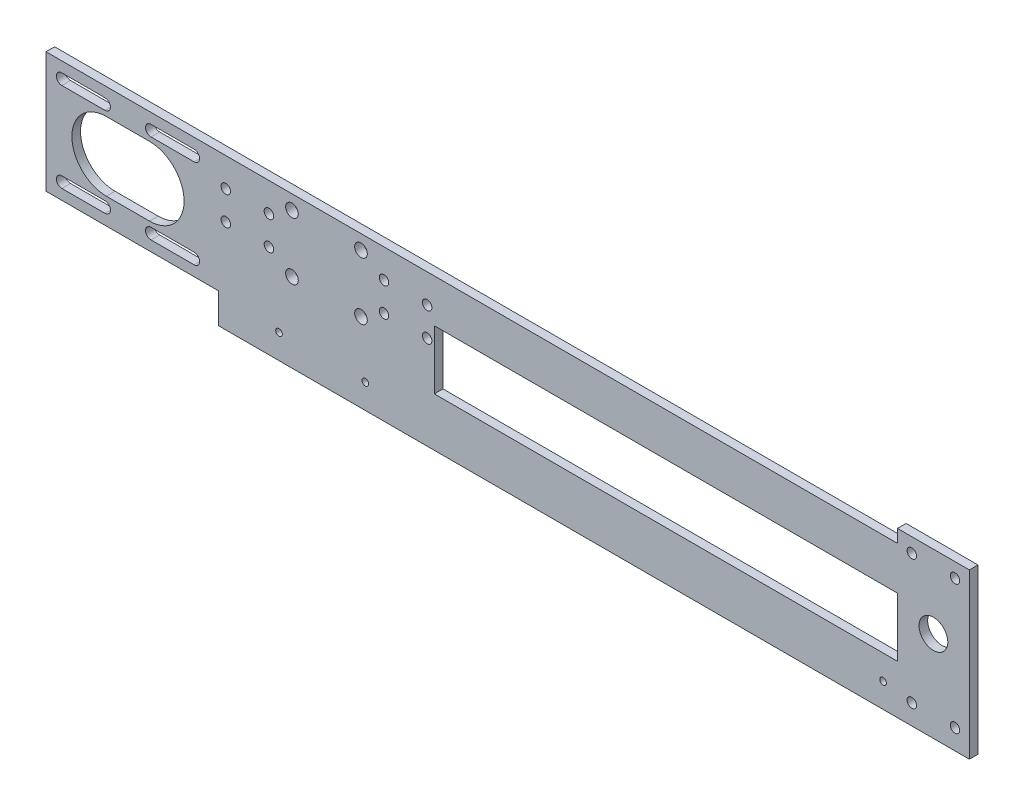
SolidWorks part; units mm, degrees
material "Thornel Mat VMA"
ref_plane "前视基准面" through (0, 0, 0) normal (0, 0, 1) x (1, 0, 0)
ref_plane "上视基准面" through (0, 0, 0) normal (0, 1, 0) x (1, 0, 0)
ref_plane "右视基准面" through (0, 0, 0) normal (1, 0, 0) x (0, 0, -1)
sketch "草图1" plane through (0, 0, 0) normal (0, 0, 1) x (1, 0, 0)
  line L1 (0, 0) -> (75, 0)
  line L2 (0, 0) -> (0, 30)
  line L3 (0, 30) -> (75, 30)
  line L4 (75, 0) -> (75, 30)
  dimension "D1" = 75
  dimension "D2" = 30
extrude "凸台-拉伸1" add sketch "草图1" along normal blind 3
sketch "草图2" plane through (0, 0, 3) normal (0, 0, 1) x (1, 0, 0)
  line L0 (0, 30) -> (75, 0)
  line L2 (25.5, 25) -> (49.5, 25)
  line L3 (25.5, 25) -> (25.5, 5)
  line L4 (25.5, 5) -> (49.5, 5)
  line L5 (49.5, 25) -> (49.5, 5)
  line L6 (25.5, 25) -> (49.5, 5) construction
  line L7 (25.5, 5) -> (49.5, 25) construction
  point P4 (37.5, 15)
  dimension "D1" = 24
  dimension "D2" = 20
sketch "草图3" plane through (0, 0, 3) normal (0, 0, 1) x (1, 0, 0)
  point P0 (25.5, 25)
  point P3 (49.5, 25)
  point P6 (49.5, 5)
  point P9 (25.5, 5)
hole_wizard "孔1" positions "草图3" profile "草图4" legacy end condition up to next
sketch "草图4" plane through (25.5, 25, 3) normal (1, 0, 0) x (0, -1, 0)
  line L0 (0, 0) -> (0, 3)
  line L1 (0, 3) -> (2.2, 3)
  line L2 (2.2, 3) -> (2.2, 0)
  line L3 (2.2, 0) -> (0, 0)
  line L4 (0, 110) -> (0, -10) construction
  dimension "直径" = 4.4
  dimension "深度" = 3
sketch "草图5" plane through (0, 0, 3) normal (0, 0, 1) x (1, 0, 0)
  line L0 (75, 30) -> (0, 30) construction
  line L1 (20, 0) -> (55, 0)
  line L2 (20, 0) -> (20, 30)
  line L3 (20, 30) -> (55, 30)
  line L4 (55, 0) -> (55, 30)
  line L5 (20, 0) -> (55, 30) construction
  line L6 (20, 30) -> (55, 0) construction
  line L7 (0, 15) -> (20, 15)
  line L8 (0, 30) -> (0, 0) construction
  line L9 (55, 15) -> (75, 15)
  line L10 (75, 0) -> (75, 30) construction
  line L12 (2.5, 10) -> (17.5, 10)
  line L13 (2.5, 10) -> (2.5, 20)
  line L14 (2.5, 20) -> (17.5, 20)
  line L15 (17.5, 10) -> (17.5, 20)
  line L16 (2.5, 10) -> (17.5, 20) construction
  line L17 (2.5, 20) -> (17.5, 10) construction
  line L18 (57.5, 10) -> (72.5, 10)
  line L19 (57.5, 10) -> (57.5, 20)
  line L20 (57.5, 20) -> (72.5, 20)
  line L21 (72.5, 10) -> (72.5, 20)
  line L22 (57.5, 10) -> (72.5, 20) construction
  line L23 (57.5, 20) -> (72.5, 10) construction
  point P0 (37.5, 15)
  point P16 (10, 15)
  point P21 (65, 15)
  dimension "D1" = 35
  dimension "D2" = 15
  dimension "D3" = 10
  dimension "D4" = 15
  dimension "D5" = 10
sketch "草图6" plane through (0, 0, 3) normal (0, 0, 1) x (1, 0, 0)
  point P0 (2.5, 20)
  point P3 (17.5, 20)
  point P6 (17.5, 10)
  point P9 (2.5, 10)
  point P12 (57.5, 10)
  point P15 (57.5, 20)
  point P18 (72.5, 20)
  point P21 (72.5, 10)
hole_wizard "孔2" positions "草图6" profile "草图7" legacy end condition up to next
sketch "草图7" plane through (2.5, 20, 3) normal (1, 0, 0) x (0, -1, 0)
  line L0 (0, 0) -> (0, 3)
  line L1 (0, 3) -> (1.65, 3)
  line L2 (1.65, 3) -> (1.65, 0)
  line L3 (1.65, 0) -> (0, 0)
  line L4 (0, 110) -> (0, -10) construction
  dimension "直径" = 3.3
  dimension "深度" = 3
sketch "草图8" plane through (0, 0, 0) normal (0, 0, -1) x (-1, 0, 0)
  line L1 (0, 30) -> (45, 30)
  line L2 (0, 30) -> (0, -12)
  line L3 (0, -12) -> (45, -12)
  line L4 (45, 30) -> (45, -12)
  dimension "D1" = 45
  dimension "D2" = 42
extrude "凸台-拉伸2" add sketch "草图8" against normal blind 3
sketch "草图9" plane through (0, 0, 3) normal (0, 0, 1) x (1, 0, 0)
  line L0 (0, -12) -> (-45, -12) construction
  line L1 (-45, 30) -> (-3, 30)
  line L2 (-45, 30) -> (-45, -12)
  line L3 (-45, -12) -> (-3, -12)
  line L4 (-3, 30) -> (-3, -12)
  line L5 (-45, 30) -> (-3, -12)
  line L7 (-39.5, 24.5) -> (-8.5, 24.5)
  line L8 (-39.5, 24.5) -> (-39.5, -6.5)
  line L9 (-39.5, -6.5) -> (-8.5, -6.5)
  line L10 (-8.5, 24.5) -> (-8.5, -6.5)
  line L11 (-39.5, 24.5) -> (-8.5, -6.5) construction
  line L12 (-39.5, -6.5) -> (-8.5, 24.5) construction
  point P7 (-24, 9)
  dimension "D1" = 42
  dimension "D2" = 31
sketch "草图10" plane through (0, 0, 3) normal (0, 0, 1) x (1, 0, 0)
  point P0 (-39.5, 24.5)
  point P3 (-8.5, 24.5)
  point P6 (-8.5, -6.5)
  point P9 (-39.5, -6.5)
hole_wizard "孔3" positions "草图10" profile "草图11" legacy end condition up to next
sketch "草图11" plane through (-39.5, 24.5, 3) normal (1, 0, 0) x (0, -1, 0)
  line L0 (0, 0) -> (0, 3)
  line L1 (0, 3) -> (1.9, 3)
  line L2 (1.9, 3) -> (1.9, 0)
  line L3 (1.9, 0) -> (0, 0)
  line L4 (0, 110) -> (0, -10) construction
  dimension "直径" = 3.8
  dimension "深度" = 3
sketch "草图12" plane through (0, 0, 0) normal (0, 0, -1) x (-1, 0, 0)
  circle A0 centre (24, 9) radius 11.5
  dimension "D1" = 23
sketch "草图13" plane through (0, 0, 0) normal (0, 0, -1) x (-1, 0, 0)
  line L0 (45, -12) -> (3, -12) construction
  line L1 (45, 30) -> (60, 30)
  line L2 (45, 30) -> (45, -12)
  line L3 (45, -12) -> (60, -12)
  line L4 (60, 30) -> (60, -12)
  dimension "D1" = 15
extrude "凸台-拉伸3" add sketch "草图13" against normal blind 3
sketch "草图14" plane through (0, 0, 0) normal (0, 0, -1) x (-1, 0, 0)
  line L0 (39.5, -6.5) -> (8.5, -6.5) construction
  line L1 (39.5, 24.5) -> (54.5, 24.5)
  line L2 (39.5, 24.5) -> (39.5, -6.5)
  line L3 (39.5, -6.5) -> (54.5, -6.5)
  line L4 (54.5, 24.5) -> (54.5, -6.5)
  line L5 (39.5, 24.5) -> (8.5, 24.5) construction
  line L7 (8.5, 26.4) -> (23.5, 26.4)
  line L8 (8.5, 26.4) -> (8.5, 22.6)
  line L9 (8.5, 22.6) -> (23.5, 22.6)
  line L10 (23.5, 26.4) -> (23.5, 22.6)
  line L11 (8.5, -4.6) -> (23.5, -4.6)
  line L12 (8.5, -4.6) -> (8.5, -8.4)
  line L13 (8.5, -8.4) -> (23.5, -8.4)
  line L14 (23.5, -4.6) -> (23.5, -8.4)
  line L15 (39.5, 26.4) -> (54.5, 26.4)
  line L16 (39.5, 26.4) -> (39.5, 22.6)
  line L17 (39.5, 22.6) -> (54.5, 22.6)
  line L18 (54.5, 26.4) -> (54.5, 22.6)
  line L19 (39.5, -4.6) -> (54.5, -4.6)
  line L20 (39.5, -4.6) -> (39.5, -8.4)
  line L21 (39.5, -8.4) -> (54.5, -8.4)
  line L22 (54.5, -4.6) -> (54.5, -8.4)
  circle A0 centre (23.5, 24.5) radius 1.9
  circle A1 centre (54.5, 24.5) radius 1.9
  circle A2 centre (54.5, -6.5) radius 1.9
  circle A3 centre (23.5, -6.5) radius 1.9
  circle A4 centre (8.5, 24.5) radius 1.9
  circle A5 centre (8.5, -6.5) radius 1.9
  circle A6 centre (39.5, 24.5) radius 1.9
  circle A7 centre (39.5, -6.5) radius 1.9
  circle M6 centre (39.5, 24.5) radius 1.9
  circle M7 centre (8.5, 24.5) radius 1.9
  circle M8 centre (8.5, -6.5) radius 1.9
  circle M9 centre (39.5, -6.5) radius 1.9
  dimension "D2" = 3.8
  dimension "D3" = 3.8
  dimension "D4" = 3.8
  dimension "D5" = 3.8
  dimension "D8" = 3.8
  dimension "D9" = 3.8
  dimension "D10" = 3.8
  dimension "D11" = 3.8
  dimension "D1" = 15
  dimension "D6" = 15
  dimension "D7" = 15
extrude "切除-拉伸3" cut sketch "草图14" against normal blind 3 contours A0 L7 L9 M7 | L10 A0 | L8 M7 | A3 L11 L13 M8 | L12 M8 | L14 A3 | L14 A3 | L12 M8 | L8 M7 | L10 A0 | A1 L15 L1 M6 | A1 L1 L17 M6 | L1 L2 M6 | L16 L1 M6 | L16 L2 M6 | L4 A1 L18 | L1 A1 L4 | L18 A1 L1 | A2 L19 L3 M9 | A2 L3 L21 M9 | L3 A2 L22 | L4 A2 L3 | L22 A2 L4 | L3 L20 M9 | L2 L3 M9 | L20 L2 M9
sketch "草图16" plane through (0, 0, 0) normal (0, 0, -1) x (-1, 0, 0)
  line L0 (24, 9) -> (39, 9)
  line L1 (39.5, 24.5) -> (39.5, -6.5) construction
  line L2 (24, 20.5041) -> (39.5, 20.5041)
  line L3 (24, 20.5041) -> (24, -2.4891)
  line L4 (24, -2.4891) -> (39.5, -2.4891)
  line L5 (39.5, 20.5041) -> (39.5, -2.4891)
  circle A0 centre (39, 9) radius 11.5
  circle A1 centre (24, 9) radius 11.5041
  dimension "D2" = 23
  dimension "D3" = 23.0082
  dimension "D1" = 15
extrude "切除-拉伸5" cut sketch "草图16" against normal blind 3
sketch "草图17" plane through (0, 0, 0) normal (0, 0, -1) x (-1, 0, 0)
  line L0 (24, 20.5041) -> (24, -2.5041)
  circle A0 centre (24, 9) radius 11.5041
  line M1 (24, -2.4891) -> (24, 20.5041)
extrude "切除-拉伸6" cut sketch "草图17" against normal blind 3 contours A0 L0 M1
sketch "草图18" plane through (0, 0, 0) normal (0, 0, -1) x (-1, 0, 0)
  line L0 (24, -2.5041) -> (-75, -2.5041)
  line L1 (-75, 0) -> (0, 0)
  line L2 (-75, 0) -> (-75, -2.5041)
  line L3 (0, 0) -> (0, -2.5041)
  line L4 (24, -2.5041) -> (-236, -2.5041)
  line L5 (24, -2.5041) -> (24, -22.5041)
  line L6 (24, -22.5041) -> (-236, -22.5041)
  line L7 (-236, -2.5041) -> (-236, -22.5041)
  line L8 (0, 0) -> (0, -12) construction
  line L9 (0, -2.5041) -> (0, -22.5041)
  line L10 (-75, -2.5041) -> (-75, -22.5041)
  line L11 (-236, -5.5041) -> (24, -5.5041)
  line L12 (-236, -5.5041) -> (-236, -22.5041)
  line L13 (-236, -22.5041) -> (24, -22.5041)
  line L14 (24, -5.5041) -> (24, -22.5041)
  circle A0 centre (24, 9) radius 11.5
  line M37 (-75, 0) -> (0, 0)
  line M38 (0, 0) -> (0, -12)
  dimension "D1" = 23
  dimension "D2" = 99
  dimension "D3" = 260
  dimension "D4" = 20
  dimension "D5" = 17
extrude "凸台-拉伸4" add sketch "草图18" against normal blind 3 contours L2 L0 M37 M38 | L10 L11 L0 M38 | L11 L10 L6 L9 | L11 L7 L6 L10
sketch "草图19" plane through (0, 0, 3) normal (0, 0, 1) x (1, 0, 0)
  line L0 (0, -22.5041) -> (236, -22.5041) construction
  line L1 (236, -5.5041) -> (46, -5.5041)
  line L2 (236, -5.5041) -> (236, -22.5041)
  line L3 (236, -22.5041) -> (46, -22.5041)
  line L4 (46, -5.5041) -> (46, -22.5041)
  line L5 (236, -14.0041) -> (46, -14.0041)
  point P9 (231, -14.0041)
  point P10 (51, -14.0041)
  dimension "D1" = 190
  dimension "D2" = 5
  dimension "D3" = 5
sketch "草图20" plane through (0, 0, 3) normal (0, 0, 1) x (1, 0, 0)
  point P0 (80, -14.0041)
  point P2 (260, -14.0041)
  point P4 (231, -14.0041)
  point P7 (51, -14.0041)
hole_wizard "孔4" positions "草图20" profile "草图21" legacy
sketch "草图21" plane through (51, -14.0041, 3) normal (1, 0, 0) x (0, -1, 0)
  line L0 (0, 0) -> (0, 3)
  line L1 (0, 3) -> (1.15, 3)
  line L2 (1.15, 3) -> (1.15, 0)
  line L3 (1.15, 0) -> (0, 0)
  line L4 (0, 110) -> (0, -10) construction
  dimension "直径" = 2.3
  dimension "深度" = 3
sketch "草图22" plane through (0, 0, 0) normal (0, 0, -1) x (-1, 0, 0)
  line L1 (-236, 19.4959) -> (-261, 19.4959)
  line L2 (-236, 19.4959) -> (-236, -22.5041)
  line L3 (-236, -22.5041) -> (-261, -22.5041)
  line L4 (-261, 19.4959) -> (-261, -22.5041)
  line L5 (-236, -5.5041) -> (-236, -22.5041) construction
  line L6 (-236, -22.5041) -> (-46, -22.5041) construction
  dimension "D1" = 42
  dimension "D2" = 25
extrude "凸台-拉伸5" add sketch "草图22" against normal up to vertex (3 mm away) up to point (236, -22.5041, 3)
sketch "草图23" plane through (0, 0, 0) normal (0, 0, -1) x (-1, 0, 0)
  line L0 (-261, 19.4959) -> (-261, -22.5041) construction
  line L1 (-261, 19.4959) -> (-236, 19.4959)
  line L2 (-261, 19.4959) -> (-261, -5.5041)
  line L3 (-261, -5.5041) -> (-236, -5.5041)
  line L4 (-236, 19.4959) -> (-236, -5.5041)
  line L5 (-236, -5.5041) -> (-236, 19.4959) construction
  line L6 (-236, 19.4959) -> (-261, 19.4959) construction
  line L7 (-236, 19.4959) -> (-261, -5.5041)
  line L8 (-248.5, 6.9959) -> (-248.5, 8.9959)
  dimension "D1" = 2
sketch "草图24" plane through (0, 0, 0) normal (0, 0, -1) x (-1, 0, 0)
  point P0 (-277.5, 6.9959)
  point P2 (-248.5, 8.9959)
hole_wizard "孔5" positions "草图24" profile "草图25" legacy end condition up to next
sketch "草图25" plane through (248.5, 8.9959, 0) normal (1, 0, 0) x (0, 1, 0)
  line L0 (0, 0) -> (0, 3)
  line L1 (0, 3) -> (5, 3)
  line L2 (5, 3) -> (5, 0)
  line L3 (5, 0) -> (0, 0)
  line L4 (0, 110) -> (0, -10) construction
  dimension "直径" = 10
  dimension "深度" = 3
sketch "草图26" plane through (0, 0, 0) normal (0, 0, -1) x (-1, 0, 0)
  line L1 (-261, -10.5041) -> (-251, -10.5041)
  line L2 (-261, -10.5041) -> (-261, -20.5041)
  line L3 (-261, -20.5041) -> (-251, -20.5041)
  line L4 (-251, -10.5041) -> (-251, -20.5041)
  line L5 (-261, -10.5041) -> (-251, -20.5041)
  line L6 (-236, -10.5041) -> (-246, -10.5041)
  line L7 (-236, -10.5041) -> (-236, -20.5041)
  line L8 (-236, -20.5041) -> (-246, -20.5041)
  line L9 (-246, -10.5041) -> (-246, -20.5041)
  line L10 (-236, -10.5041) -> (-246, -20.5041)
  line L11 (-261, -5.5041) -> (-236, -5.5041) construction
  line L12 (-261, 19.4959) -> (-261, -22.5041) construction
  line L13 (-236, -5.5041) -> (-236, -22.5041) construction
  dimension "D1" = 10
  dimension "D2" = 10
  dimension "D3" = 10
  dimension "D4" = 10
  dimension "D5" = 5
  dimension "D6" = 5
sketch "草图29" plane through (0, 0, 0) normal (0, 0, -1) x (-1, 0, 0)
  line L0 (-261, -10.5041) -> (-251, -20.5041) construction
  line L1 (-236, -10.5041) -> (-246, -20.5041) construction
  point P0 (-285, -15.5041)
  point P2 (-270, -15.5041)
  point P3 (-285, -15.5041)
  point P6 (-285, -15.5041)
  point P9 (-256, -15.5041)
  point P13 (-241, -15.5041)
hole_wizard "孔7" positions "草图29" profile "草图30" legacy end condition up to next
sketch "草图30" plane through (241, -15.5041, 0) normal (1, 0, 0) x (0, 1, 0)
  line L0 (0, 0) -> (0, 3.001)
  line L1 (0, 3.001) -> (1.65, 3.001)
  line L2 (1.65, 3.001) -> (1.65, 0)
  line L3 (1.65, 0) -> (0, 0)
  line L4 (0, 110) -> (0, -10) construction
  dimension "直径" = 3.3
  dimension "深度" = 3.001
sketch "草图31" plane through (0, 0, 0) normal (0, 0, -1) x (-1, 0, 0)
  line L0 (-236, 19.4959) -> (-236, -5.5041) construction
  line L1 (-261, 19.4959) -> (-236, 19.4959)
  line L2 (-261, 19.4959) -> (-261, 34.4959)
  line L3 (-261, 34.4959) -> (-236, 34.4959)
  line L4 (-236, 19.4959) -> (-236, 34.4959)
  line L5 (-261, 19.4959) -> (-261, -5.5041) construction
  line L6 (-261, 19.4959) -> (-236, 19.4959) construction
  dimension "D1" = 15
extrude "凸台-拉伸6" add sketch "草图31" against normal blind 3
sketch "草图32" plane through (0, 0, 0) normal (0, 0, -1) x (-1, 0, 0)
  line L0 (-261, 34.4959) -> (-261, -22.5041) construction
  line L1 (-261, 34.4959) -> (-251, 34.4959)
  line L2 (-261, 34.4959) -> (-261, 24.4959)
  line L3 (-261, 24.4959) -> (-251, 24.4959)
  line L4 (-251, 34.4959) -> (-251, 24.4959)
  line L5 (-236, 34.4959) -> (-261, 34.4959) construction
  line L6 (-236, -5.5041) -> (-236, 34.4959) construction
  line L7 (-236, 34.4959) -> (-246, 34.4959)
  line L8 (-236, 34.4959) -> (-236, 24.4959)
  line L9 (-236, 24.4959) -> (-246, 24.4959)
  line L10 (-246, 34.4959) -> (-246, 24.4959)
  line L11 (-261, 34.4959) -> (-251, 24.4959)
  line L12 (-236, 34.4959) -> (-246, 24.4959)
  dimension "D1" = 10
  dimension "D2" = 10
  dimension "D3" = 10
  dimension "D4" = 10
sketch "草图33" plane through (0, 0, 0) normal (0, 0, -1) x (-1, 0, 0)
  line L0 (-261, 34.4959) -> (-251, 24.4959) construction
  line L1 (-236, 34.4959) -> (-246, 24.4959) construction
  point P0 (-285, 29.4959)
  point P2 (-270, 29.4959)
  point P3 (-256, 29.4959)
  point P7 (-241, 29.4959)
hole_wizard "孔8" positions "草图33" profile "草图34" legacy end condition up to next
sketch "草图34" plane through (241, 29.4959, 0) normal (1, 0, 0) x (0, 1, 0)
  line L0 (0, 0) -> (0, 3)
  line L1 (0, 3) -> (1.65, 3)
  line L2 (1.65, 3) -> (1.65, 0)
  line L3 (1.65, 0) -> (0, 0)
  line L4 (0, 110) -> (0, -10) construction
  dimension "直径" = 3.3
  dimension "深度" = 3
sketch "草图35" plane through (0, 0, 0) normal (0, 0, -1) x (-1, 0, 0)
  line L0 (24, 9) -> (-261, 9)
  line L1 (-236, -22.5041) -> (-46, -22.5041) construction
  line L2 (-261, 19.4959) -> (-261, -5.5041) construction
sketch "草图36" plane through (0, 0, 0) normal (0, 0, -1) x (-1, 0, 0)
  line L0 (-236, 19.4959) -> (-236, -5.5041) construction
  line L1 (-75, 30) -> (-236, 30)
  line L2 (-75, 30) -> (-75, 15)
  line L3 (-75, 15) -> (-236, 15)
  line L4 (-236, 30) -> (-236, 15)
  dimension "D1" = 15
extrude "凸台-拉伸7" add sketch "草图36" against normal blind 3
sketch "草图37" plane through (0, 0, 0) normal (0, 0, -1) x (-1, 0, 0)
  line L0 (-51, -14.0041) -> (-21, -14.0041)
  dimension "D1" = 30
sketch "草图38" plane through (0, 0, 0) normal (0, 0, -1) x (-1, 0, 0)
  point P0 (-21, -14.0041)
hole_wizard "孔9" positions "草图38" profile "草图39" legacy end condition up to next
sketch "草图39" plane through (21, -14.0041, 0) normal (1, 0, 0) x (0, 1, 0)
  line L0 (0, 0) -> (0, 3)
  line L1 (0, 3) -> (1.15, 3)
  line L2 (1.15, 3) -> (1.15, 0)
  line L3 (1.15, 0) -> (0, 0)
  line L4 (0, 110) -> (0, -10) construction
  dimension "直径" = 2.3
  dimension "深度" = 3
sketch "草图40" plane through (0, 0, 0) normal (0, 0, -1) x (-1, 0, 0)
  line L0 (39.5, -6.5) -> (8.5, 24.5) construction
  line L1 (24, 21) -> (39, 21)
  line L2 (24, -3) -> (39, -3)
  circle A0 centre (24, 9) radius 12
  circle A1 centre (39, 9) radius 12
  dimension "D1" = 24
  dimension "D2" = 24
extrude "切除-拉伸7" cut sketch "草图40" against normal blind 10 contours A1 A0 | A0 A1 | A1 L1 A0 | A1 A0 | A1 A0 L2
